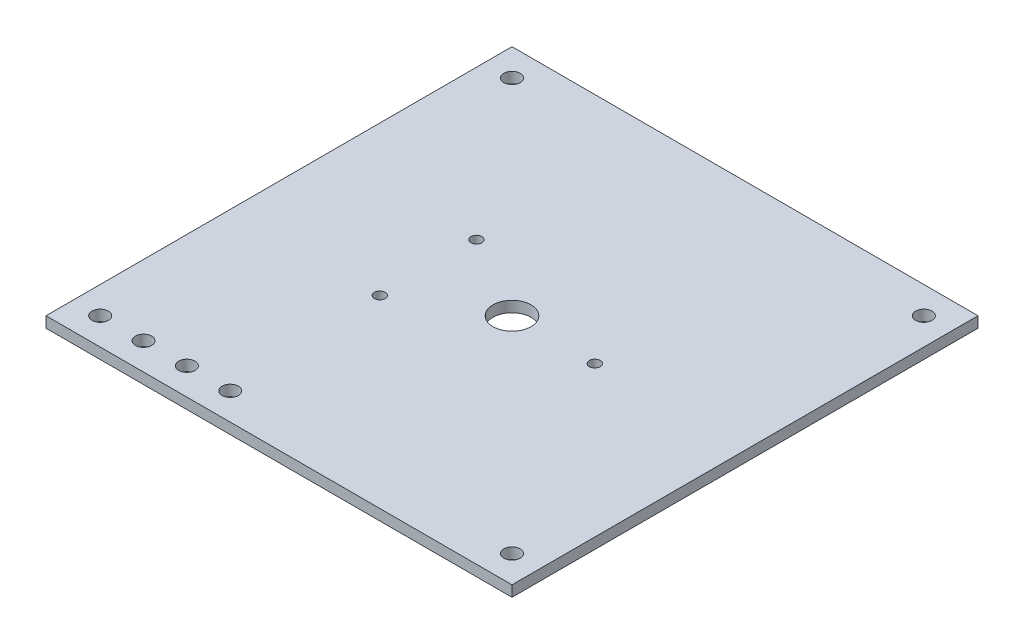
SolidWorks part; units mm, degrees
ref_plane "Front Plane" through (0, 0, 0) normal (0, 0, 1) x (1, 0, 0)
ref_plane "Top Plane" through (0, 0, 0) normal (0, 1, 0) x (1, 0, 0)
ref_plane "Right Plane" through (0, 0, 0) normal (1, 0, 0) x (0, 0, -1)
sketch "Sketch1" plane through (0, 0, 0) normal (0, 1, 0) x (1, 0, 0)
  line L1 (136.525, -136.525) -> (-136.525, -136.525)
  line L2 (136.525, -136.525) -> (136.525, 136.525)
  line L3 (136.525, 136.525) -> (-136.525, 136.525)
  line L4 (-136.525, -136.525) -> (-136.525, 136.525)
  line L5 (136.525, -136.525) -> (-136.525, 136.525) construction
  line L6 (136.525, 136.525) -> (-136.525, -136.525) construction
  circle A0 centre (0, 0) radius 11.1125
  point P0 (0, 0)
  dimension "D3" = 0
  dimension "D1" = 273.05
  dimension "D2" = 273.05
extrude "Boss-Extrude1" add sketch "Sketch1" along normal blind 6.35
sketch "Sketch2" plane through (0, 6.35, 0) normal (0, 1, 0) x (-1, 0, 0)
  line L0 (0, 136.525) -> (0, -136.525) construction
  line L1 (136.525, 136.525) -> (-136.525, 136.525) construction
  line L2 (-136.525, -136.525) -> (136.525, -136.525) construction
  line L3 (136.525, 0) -> (-136.525, 0) construction
  line L4 (136.525, -136.525) -> (136.525, 136.525) construction
  line L5 (-136.525, 136.525) -> (-136.525, -136.525) construction
  circle A0 centre (120.65, -120.65) radius 4.7625
  circle A1 centre (120.65, 120.65) radius 4.7625
  circle A2 centre (-120.65, -120.65) radius 4.7625
  circle A3 centre (-120.65, 120.65) radius 4.7625
  circle A5 centre (95.25, 120.65) radius 4.7625
  circle A6 centre (69.85, 120.65) radius 4.7625
  circle A7 centre (44.45, 120.65) radius 4.7625
  dimension "D1" = 120.65
  dimension "D2" = 25.4
  dimension "D3" = 3
extrude "Cut-Extrude1" cut sketch "Sketch2" against normal through all
sketch "Sketch3" plane through (0, 6.35, 0) normal (0, 1, 0) x (-1, 0, 0)
  line L0 (49.022, -136.525) -> (49.022, 136.525) construction
  line L1 (-136.525, -136.525) -> (136.525, -136.525) construction
  line L2 (136.525, 136.525) -> (-136.525, 136.525) construction
  circle A0 centre (49.022, -28.194) radius 3.175
  circle A1 centre (49.022, 28.446) radius 3.175
  circle A2 centre (-48.514, 0) radius 3.175
  dimension "D1" = 2
  dimension "D4" = 48.514
  dimension "D2" = 49.022
  dimension "D3" = 28.194
extrude "Cut-Extrude4" cut sketch "Sketch3" against normal through all
